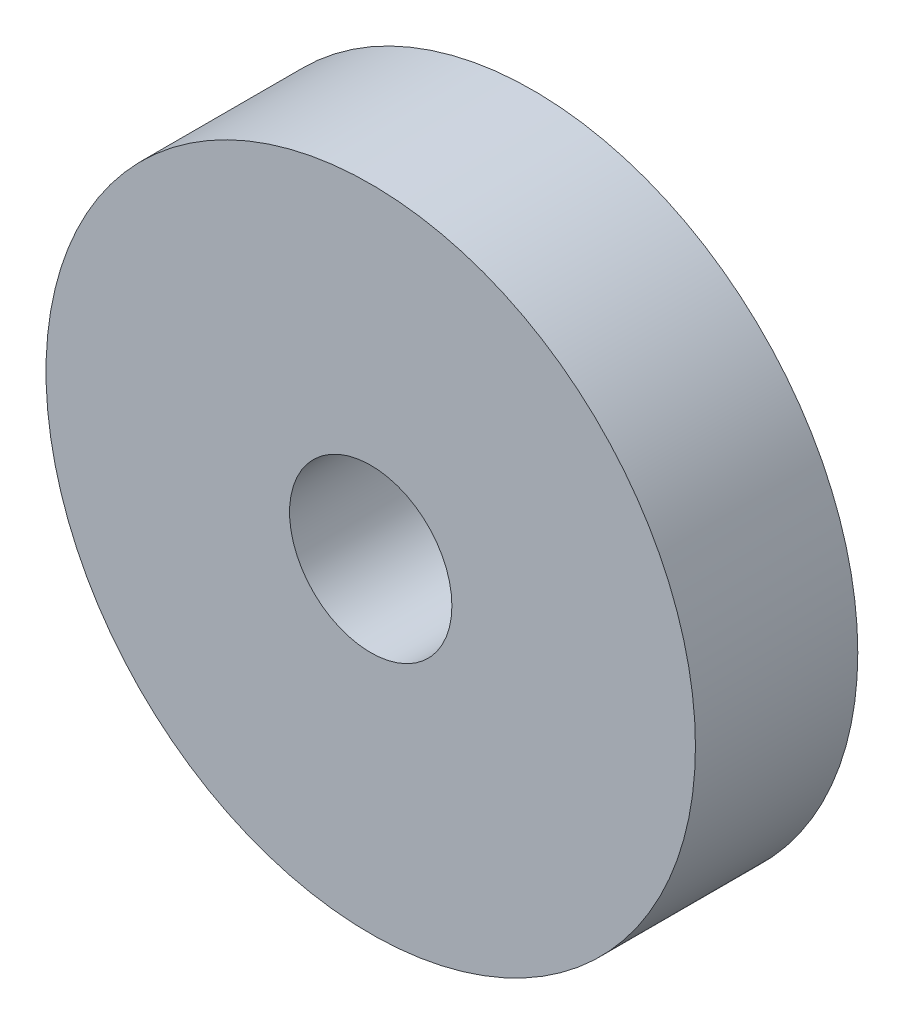
SolidWorks part; units mm, degrees
ref_plane "Front Plane" through (0, 0, 0) normal (0, 0, 1) x (1, 0, 0)
ref_plane "Top Plane" through (0, 0, 0) normal (0, 1, 0) x (1, 0, 0)
ref_plane "Right Plane" through (0, 0, 0) normal (1, 0, 0) x (0, 0, -1)
sketch "Sketch1" plane through (0, 0, 0) normal (0, 0, 1) x (1, 0, 0)
  circle A0 centre (0, 0) radius 5
  circle A1 centre (0, 0) radius 20
  dimension "D1" = 40
  dimension "D2" = 10
extrude "Boss-Extrude1" add sketch "Sketch1" along normal blind 10
